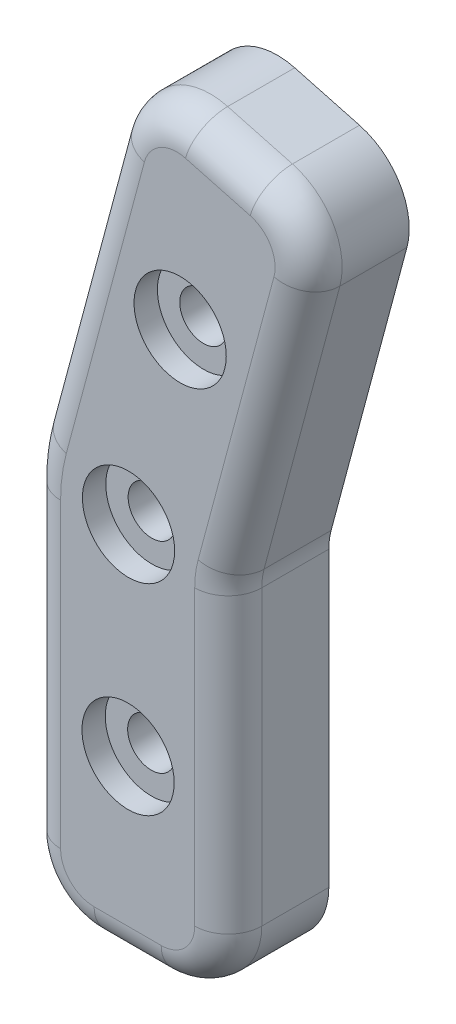
SolidWorks part; units mm, degrees
material "Delrin 2700 NC010, Low Viscosity Acetal Copolymer (SS)"
ref_plane "Front Plane" through (0, 0, 0) normal (0, 0, 1) x (1, 0, 0)
ref_plane "Top Plane" through (0, 0, 0) normal (0, 1, 0) x (1, 0, 0)
ref_plane "Right Plane" through (0, 0, 0) normal (1, 0, 0) x (0, 0, -1)
sketch "Sketch1" plane through (0, 0, 0) normal (0, 0, 1) x (1, 0, 0)
  line L1 (-9.525, -17.4625) -> (9.525, -17.4625)
  line L2 (-9.525, -17.4625) -> (-9.525, 17.4625)
  line L3 (-9.525, 17.4625) -> (9.525, 17.4625)
  line L4 (9.525, -17.4625) -> (9.525, 17.4625)
  line L5 (-9.525, -17.4625) -> (9.525, 17.4625) construction
  line L6 (-9.525, 17.4625) -> (9.525, -17.4625) construction
  point P0 (0, 0)
  dimension "D1" = 19.05
  dimension "D2" = 34.925
extrude "Boss-Extrude1" add sketch "Sketch1" along normal mid plane 9.525
sketch "Sketch2" plane through (0, 0, 4.7625) normal (0, 0, 1) x (1, 0, 0)
  line L0 (9.525, 17.4625) -> (18.5643, 51.1975)
  line L1 (18.5643, 51.1975) -> (0.1634, 56.128)
  line L2 (0.1634, 56.128) -> (-8.8759, 22.393)
  line L3 (-8.8759, 22.393) -> (9.525, 17.4625)
  line L4 (9.525, 17.4625) -> (-9.525, 17.4625) construction
  line L5 (9.525, -17.4625) -> (9.525, 17.4625) construction
  dimension "D1" = 34.925
  dimension "D2" = 165
extrude "Boss-Extrude2" add sketch "Sketch2" against normal up to surface (9.525 mm away) separate body up to face at (0, 0, -4.7625)
sketch "Sketch3" plane through (0, 0, 4.7625) normal (0, 0, 1) x (1, 0, 0)
  line L0 (-8.8759, 22.393) -> (9.525, 17.4625) construction
  line L1 (9.525, 17.4625) -> (-9.525, 17.4625) construction
  line L2 (-8.8759, 22.393) -> (9.525, 17.4625)
  line L3 (9.525, 17.4625) -> (-9.525, 17.4625)
  arc A0 (-8.8759, 22.393) -> (-9.525, 17.4625) centre (9.525, 17.4625) ccw
extrude "Boss-Extrude3" add sketch "Sketch3" against normal up to surface (9.525 mm away) up to face at (0, 0, -4.7625)
hole_wizard "CBORE for #8 Button Head Cap Screw1" positions "Sketch4" profile "Sketch5" counterbore size "#8" standard "ANSI Inch" end condition through all
sketch "Sketch4" plane through (0, 0, 4.7625) normal (0, 0, 1) x (1, 0, 0)
  line L0 (9.525, 17.4625) -> (-9.362, 19.949) construction
  line L2 (0.0815, 18.7058) -> (9.3638, 53.6627) construction
  line L3 (18.5643, 51.1975) -> (0.1634, 56.128) construction
  line L5 (0, -17.4625) -> (0.0815, 18.7058) construction
  line L6 (-9.525, -17.4625) -> (9.525, -17.4625) construction
  arc A0 (-8.8759, 22.393) -> (-9.525, 17.4625) centre (9.525, 17.4625) ccw construction
  point P9 (0.0815, 18.7058)
  point P23 (4.9705, 37.1177)
  point P25 (0.0386, -0.3442)
  dimension "D1" = 19.05
  dimension "D2" = 19.05
sketch "Sketch5" plane through (0.0386, -0.3442, 4.7625) normal (1, 0, 0) x (0, -1, 0)
  line L0 (0, 0) -> (0, 9.525)
  line L1 (0, 9.525) -> (2.2479, 9.525)
  line L3 (2.2479, 9.525) -> (2.2479, 2.2098)
  line L4 (2.2479, 2.2098) -> (4.3663, 2.2098)
  line L5 (4.3663, 2.2098) -> (4.3663, 0)
  line L7 (4.3663, 0) -> (0, 0)
  line L11 (0, -6.35) -> (0, 107.95) construction
  dimension "Thru Hole Dia." = 4.4958
  dimension "Thru Hole Depth" = 9.525
  dimension "C'Bore Dia." = 8.7325
  dimension "C'Bore Depth" = 2.2098
fillet "Fillet1" radius 6.35 5 edges at (9.525, 17.4625, 0) (0.1634, 56.128, 0) (-9.525, -17.4625, 0) (9.525, -17.4625, 0) (18.5643, 51.1975, 0)
sketch "Sketch6" plane through (0, 0, -4.7625) normal (0, 0, -1) x (-1, 0, 0)
  circle A0 centre (-0.0386, -0.3442) radius 2.2479 construction
  circle A1 centre (-0.0815, 18.7058) radius 2.2479 construction
  circle A2 centre (-4.9705, 37.1177) radius 2.2479 construction
  circle A3 centre (-0.0386, -0.3442) radius 2.2479
  circle A4 centre (-0.0815, 18.7058) radius 2.2479
  circle A5 centre (-4.9705, 37.1177) radius 2.2479
  circle A6 centre (-4.9705, 37.1177) radius 3.175
  circle A7 centre (-0.0815, 18.7058) radius 3.175
  circle A8 centre (-0.0386, -0.3442) radius 3.175
  dimension "D1" = 6.35
extrude "Cut-Extrude1" cut sketch "Sketch6" against normal blind 3.175
fillet "Fillet2" radius 3.175 12 edges at (9.5793, 17.4553, 4.7625) (9.525, 2.757, 4.7625) (7.6651, -15.6026, 4.7625) (0, -17.4625, 4.7625) (-7.6651, -15.6026, 4.7625) (-9.525, 3.175, 4.7625) (-9.362, 19.949, 4.7625) (-5.178, 36.1937, 4.7625) (1.4785, 53.8501, 4.7625) (9.3638, 53.6627, 4.7625) (16.2864, 49.8823, 4.7625) (13.3311, 31.6669, 4.7625)
equation "\"D2@Sketch4\"=\"D1@Sketch4\""
equation "\"D2@Sketch1\"=1.250in+.125"
equation "\"D1@Sketch2\"=1.250in+.125"
